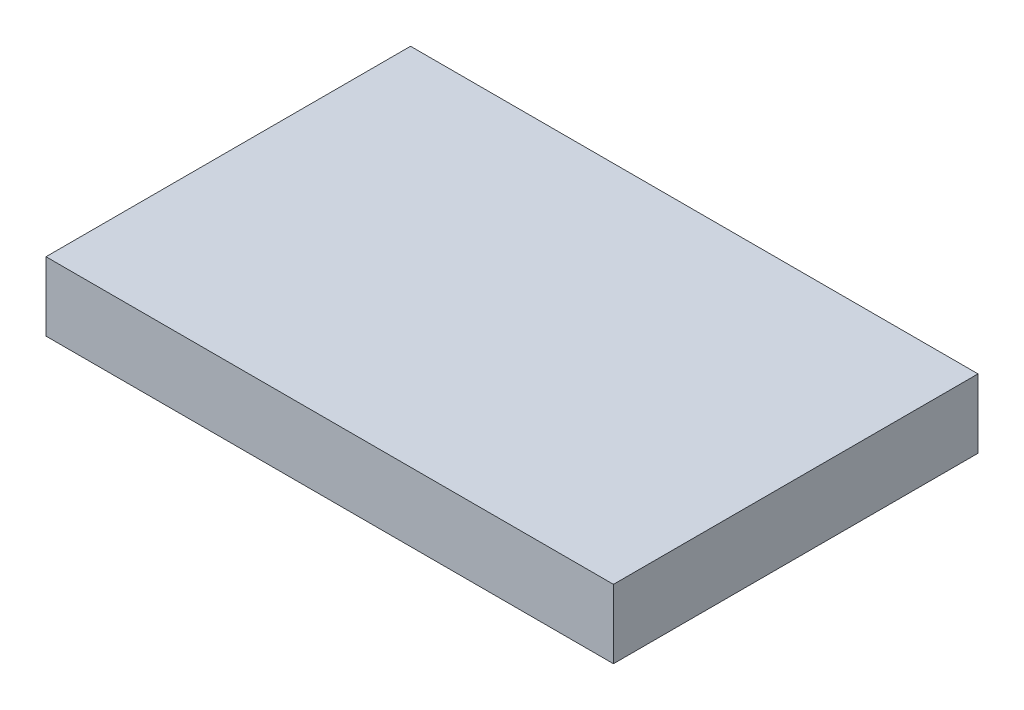
SolidWorks part; units mm, degrees
material "ABS"
ref_plane "Płaszczyzna przednia" through (0, 0, 0) normal (0, 0, 1) x (1, 0, 0)
ref_plane "Płaszczyzna górna" through (0, 0, 0) normal (0, 1, 0) x (1, 0, 0)
ref_plane "Płaszczyzna prawa" through (0, 0, 0) normal (1, 0, 0) x (0, 0, -1)
sketch "Szkic1" plane through (0, 0, 0) normal (0, 1, 0) x (1, 0, 0)
  line L1 (-41.25, 26.5) -> (41.25, 26.5)
  line L2 (-41.25, 26.5) -> (-41.25, -26.5)
  line L3 (-41.25, -26.5) -> (41.25, -26.5)
  line L4 (41.25, 26.5) -> (41.25, -26.5)
  line L5 (-41.25, 26.5) -> (41.25, -26.5) construction
  line L6 (-41.25, -26.5) -> (41.25, 26.5) construction
  point P0 (0, 0)
  dimension "D1" = 82.5
  dimension "D2" = 53
extrude "Dodanie-wyciągnięcie1" add sketch "Szkic1" along normal blind 10
